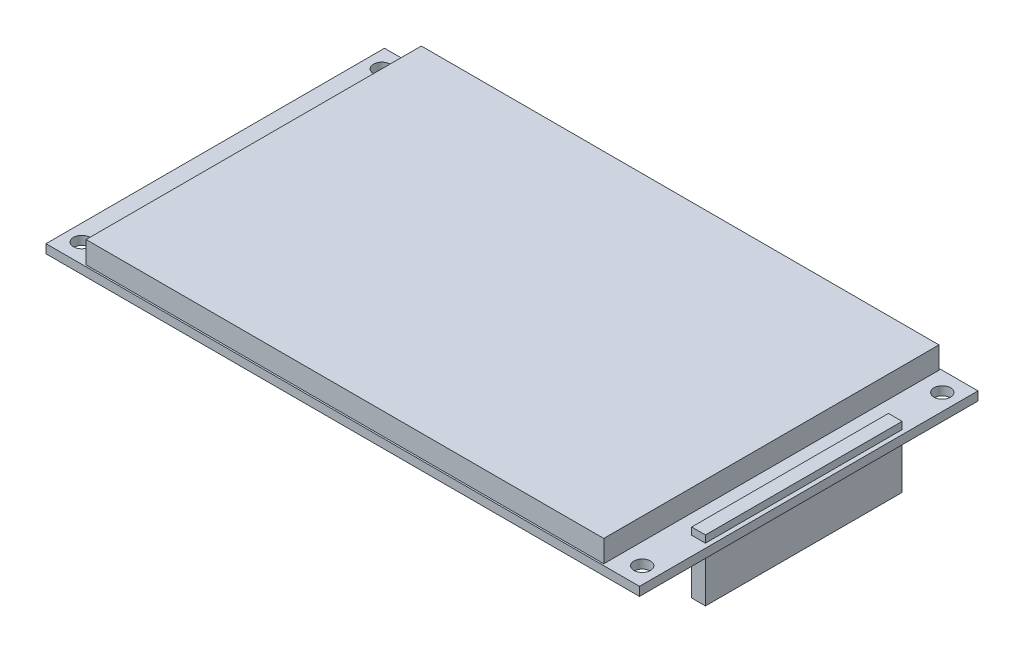
SolidWorks part; units mm, degrees
ref_plane "Piano frontale" through (0, 0, 0) normal (0, 0, 1) x (1, 0, 0)
ref_plane "Piano superiore" through (0, 0, 0) normal (0, 1, 0) x (1, 0, 0)
ref_plane "Piano destro" through (0, 0, 0) normal (1, 0, 0) x (0, 0, -1)
sketch "Schizzo1" plane through (0, 0, 0) normal (0, 1, 0) x (1, 0, 0)
  line L1 (0, 0) -> (94.2, 0)
  line L2 (0, 0) -> (0, 61)
  line L3 (0, 61) -> (94.2, 61)
  line L4 (94.2, 0) -> (94.2, 61)
  point P4 (0, 0)
  dimension "D3" = 94.2
  dimension "D4" = 61
extrude "Estrusione-Estrusione1" add sketch "Schizzo1" along normal blind 4
sketch "Schizzo2" plane through (0, 0, 0) normal (0, -1, 0) x (1, 0, 0)
  line L0 (0, -61) -> (0, 0) construction
  line L1 (-7, -61.3) -> (101, -61.3)
  line L2 (-7, -61.3) -> (-7, 0.3)
  line L3 (-7, 0.3) -> (101, 0.3)
  line L4 (101, -61.3) -> (101, 0.3)
  point P8 (0, -30.5)
  dimension "D1" = 108
  dimension "D2" = 7
  dimension "D3" = 61.6
  dimension "D4" = 30.8
extrude "Estrusione-Estrusione2" add sketch "Schizzo2" along normal blind 1.6
sketch "Schizzo4" plane through (0, 0, 0) normal (0, 1, 0) x (1, 0, 0)
  line L0 (-7, 61.3) -> (101, 61.3) construction
  line L1 (100.2, 48.3) -> (97.7, 48.3)
  line L2 (100.2, 48.3) -> (100.2, 12.5)
  line L3 (100.2, 12.5) -> (97.7, 12.5)
  line L4 (97.7, 48.3) -> (97.7, 12.5)
  line L6 (101, 61.3) -> (101, -0.3) construction
  dimension "D1" = 35.8
  dimension "D2" = 2.5
  dimension "D3" = 0.8
  dimension "D4" = 13
extrude "Estrusione-Estrusione3" add sketch "Schizzo4" along normal blind 1.3 and the other way blind 9.9
sketch "Schizzo6" plane through (0, 0, 0) normal (0, 1, 0) x (1, 0, 0)
  line L0 (-7, 61.3) -> (101, 61.3) construction
  line L1 (101, -0.3) -> (-7, -0.3) construction
  line L3 (-7, -0.3) -> (-7, 61.3) construction
  line L4 (101, 61.3) -> (101, -0.3) construction
  circle A0 centre (-4, 57.8) radius 1.5
  circle A1 centre (-4, 3.2) radius 1.5
  circle A2 centre (98, 57.8) radius 1.5
  circle A3 centre (98, 3.2) radius 1.5
  dimension "D1" = 3
  dimension "D2" = 3
  dimension "D3" = 3
  dimension "D4" = 3
  dimension "D9" = 3
  dimension "D10" = 3
  dimension "D11" = 3
  dimension "D12" = 3
  dimension "D5" = 3.5
  dimension "D6" = 3.5
  dimension "D7" = 3.5
  dimension "D8" = 3.5
extrude "Taglio-Estrusione1" cut sketch "Schizzo6" against normal blind 2
sketch "Schizzo7" plane through (0, -1.6, 0) normal (0, -1, 0) x (1, 0, 0)
  line L1 (21, -21.2) -> (48, -21.2)
  line L2 (21, -21.2) -> (21, -4.2)
  line L3 (21, -4.2) -> (48, -4.2)
  line L4 (48, -21.2) -> (48, -4.2)
  line L5 (101, 0.3) -> (-7, 0.3) construction
  line L6 (-7, 0.3) -> (-7, -61.3) construction
  dimension "D1" = 4.5
  dimension "D2" = 17
  dimension "D3" = 27
  dimension "D4" = 28
extrude "Estrusione-Estrusione4" add sketch "Schizzo7" along normal blind 3 contours L3 L4 L1 L2
